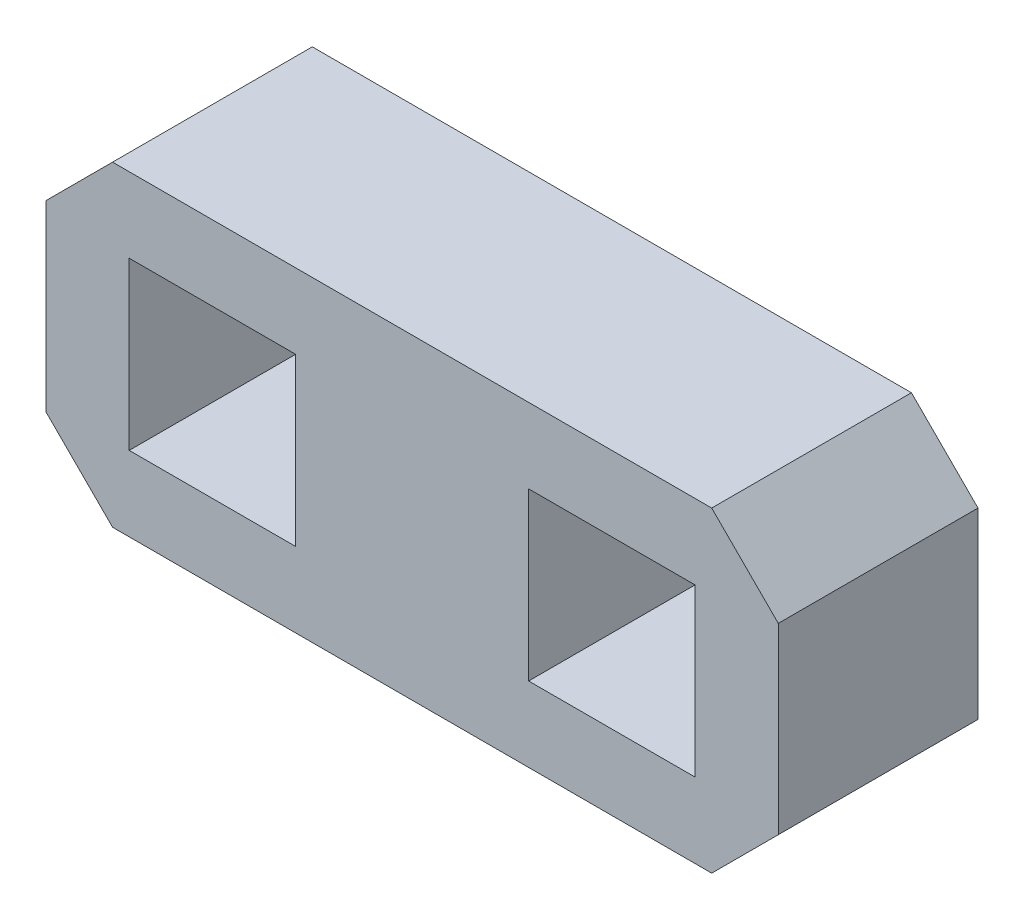
SolidWorks part; units mm, degrees
ref_plane "前视基准面" through (0, 0, 0) normal (0, 0, 1) x (1, 0, 0)
ref_plane "上视基准面" through (0, 0, 0) normal (0, 1, 0) x (1, 0, 0)
ref_plane "右视基准面" through (0, 0, 0) normal (1, 0, 0) x (0, 0, -1)
sketch "草图1" plane through (0, 0, 0) normal (0, 0, 1) x (1, 0, 0)
  line L1 (-11, -4.75) -> (11, -4.75)
  line L2 (-11, -4.75) -> (-11, 4.75)
  line L3 (-11, 4.75) -> (11, 4.75)
  line L4 (11, -4.75) -> (11, 4.75)
  line L5 (-11, -4.75) -> (11, 4.75) construction
  line L6 (-11, 4.75) -> (11, -4.75) construction
  point P0 (0, 0)
  dimension "D1" = 9.5
  dimension "D2" = 22
extrude "凸台-拉伸1" add sketch "草图1" along normal mid plane 6
sketch "草图2" plane through (0, 0, 3) normal (0, 0, 1) x (1, 0, 0)
  line L0 (11, -4.75) -> (11, 4.75) construction
  line L1 (3.5, 2.5) -> (8.5, 2.5)
  line L2 (3.5, 2.5) -> (3.5, -2.5)
  line L3 (3.5, -2.5) -> (8.5, -2.5)
  line L4 (8.5, 2.5) -> (8.5, -2.5)
  line L5 (3.5, 2.5) -> (8.5, -2.5) construction
  line L6 (3.5, -2.5) -> (8.5, 2.5) construction
  line L7 (-11, -4.75) -> (11, -4.75) construction
  point P0 (6, 0)
  dimension "D1" = 2.5
  dimension "D2" = 2.25
  dimension "D3" = 5
extrude "切除-拉伸1" cut sketch "草图2" against normal through all
mirror "镜向1" about plane through (0, 0, 0) normal (1, 0, 0) of "切除-拉伸1"
chamfer "倒角1" distance 2 angle 45 4 edges at (-11, -4.75, 0) (-11, 4.75, 0) (11, -4.75, 0) (11, 4.75, 0)
